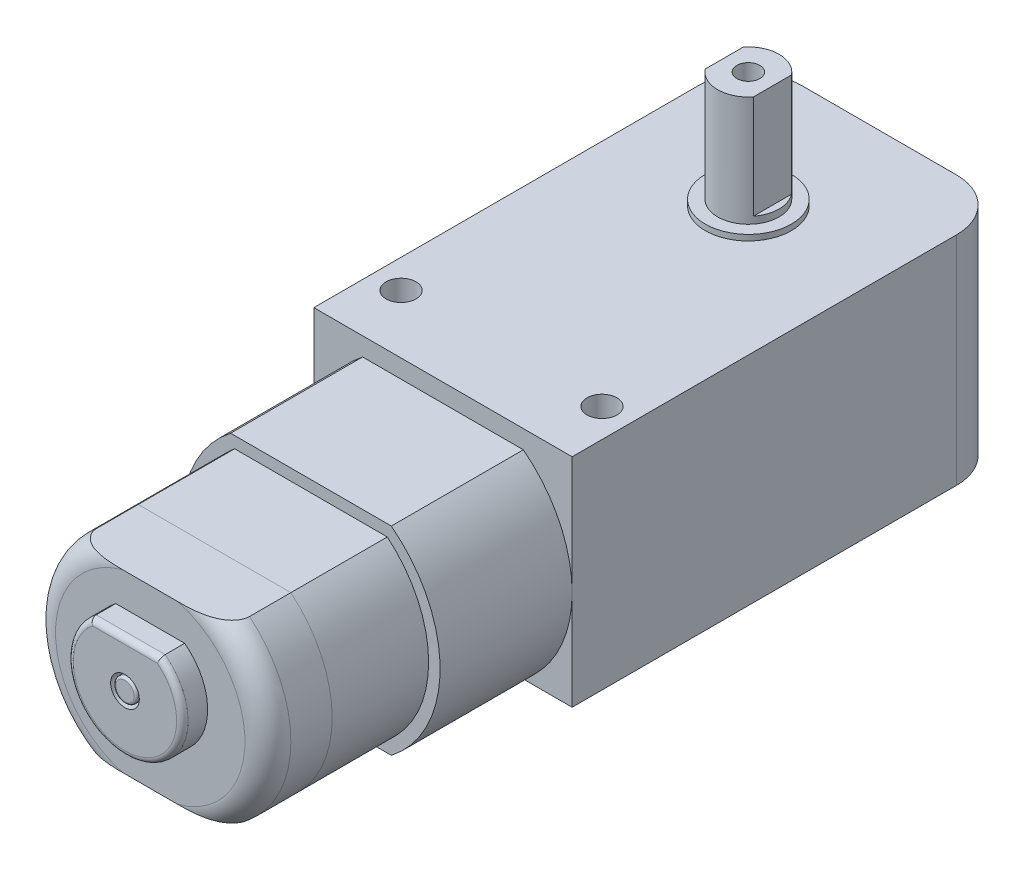
SolidWorks part; units mm, degrees
ref_plane "Front Plane" through (0, 0, 0) normal (0, 0, 1) x (1, 0, 0)
ref_plane "Top Plane" through (0, 0, 0) normal (0, 1, 0) x (1, 0, 0)
ref_plane "Right Plane" through (0, 0, 0) normal (1, 0, 0) x (0, 0, -1)
sketch "Sketch1" plane through (0, 0, 0) normal (0, 1, 0) x (1, 0, 0)
  line L1 (11.25, 19) -> (-11.25, 19)
  line L2 (11.25, 19) -> (11.25, -19)
  line L3 (11.25, -19) -> (-11.25, -19)
  line L4 (-11.25, 19) -> (-11.25, -19)
  line L5 (11.25, 19) -> (-11.25, -19) construction
  line L6 (11.25, -19) -> (-11.25, 19) construction
  point P0 (0, 0)
  dimension "D1" = 22.5
  dimension "D2" = 38
extrude "Boss-Extrude1" add sketch "Sketch1" along normal mid plane 18.9
fillet "Fillet1" radius 4.5 2 edges at (-11.25, 0, -19) (11.25, 0, -19)
sketch "Sketch2" plane through (0, 0, 19) normal (0, 0, 1) x (1, 0, 0)
  line L0 (-11.25, -9.45) -> (11.25, -9.45) construction
  line L5 (7, -9.45) -> (-7, -9.45)
  line L7 (7, 7.85) -> (-7, 7.85)
  line L9 (7, -9.45) -> (-7, 7.85) construction
  line L10 (7, 7.85) -> (-7, -9.45) construction
  line L13 (-11.25, 9.45) -> (-11.25, -9.45) construction
  arc A0 (-7, 7.85) -> (-7, -9.45) centre (-0.3224, -0.8) ccw
  arc A1 (7, 7.85) -> (7, -9.45) centre (0.3224, -0.8) cw
  point P0 (0, -0.8)
  point P5 (0, 0)
  point P10 (0, 0)
  point P11 (0, 0)
  point P12 (0, -0.8)
  point P13 (0, 0)
  point P14 (0, 0)
  point P15 (0, 0)
  point P18 (-2.3599, -0.8)
  dimension "D3" = 10.9276
  dimension "D1" = 17.3
  dimension "D2" = 14
extrude "Boss-Extrude2" add sketch "Sketch2" along normal blind 11.5
sketch "Sketch3" plane through (0, 0, 30.5) normal (0, 0, 1) x (1, 0, 0)
  line L4 (-6.6497, -8.45) -> (6.6497, -8.45)
  line L5 (6.6497, 6.85) -> (-6.6497, 6.85)
  line L6 (-6.6497, -8.45) -> (6.6497, -8.45)
  line L7 (6.6497, 6.85) -> (-6.6497, 6.85)
  arc A4 (-6.6497, 6.85) -> (-6.6497, -8.45) centre (-0.3224, -0.8) ccw
  arc A5 (6.6497, -8.45) -> (6.6497, 6.85) centre (0.3224, -0.8) ccw
  arc A6 (-6.6497, 6.85) -> (-6.6497, -8.45) centre (-0.3224, -0.8) ccw
  arc A7 (6.6497, -8.45) -> (6.6497, 6.85) centre (0.3224, -0.8) ccw
  dimension "D1" = 1
extrude "Cut-Extrude1" cut sketch "Sketch3" against normal up to surface (11.5 mm away) up to face at (0, 5.6646, 19)
sketch "Sketch4" plane through (0, 0, 0) normal (0, 1, 0) x (1, 0, 0)
  line L0 (6.75, 19) -> (-6.75, 19) construction
  line L1 (2.5, 19) -> (-2.5, 19)
  line L2 (2.5, 19) -> (2.5, 24)
  line L3 (2.5, 24) -> (-2.5, 24)
  line L4 (-2.5, 19) -> (-2.5, 24)
  line L5 (2.5, 19) -> (-2.5, 24) construction
  line L6 (2.5, 24) -> (-2.5, 19) construction
  circle A0 centre (0, 21.5) radius 1.25
  point P0 (0, 21.5)
  point P5 (-2.5, 19)
  dimension "D3" = 2.5
  dimension "D1" = 5
  dimension "D2" = 5
extrude "Boss-Extrude3" add sketch "Sketch4" along normal mid plane 2.5 contours L4 L1 L2 L3 A0
sketch "Sketch5" plane through (0, 9.45, 0) normal (0, 1, 0) x (1, 0, 0)
  line L0 (0, 24) -> (0, 0) construction
  line L1 (2.5, 24) -> (-2.5, 24) construction
  line L2 (6.75, 19) -> (-6.75, 19) construction
  circle A0 centre (0, 7.6) radius 3.75
  point P7 (0, 11.0568)
  dimension "D1" = 7.5
  dimension "D2" = 11.4
extrude "Boss-Extrude4" add sketch "Sketch5" along normal blind 0.5
sketch "Sketch6" plane through (0, 9.95, 0) normal (0, 1, 0) x (1, 0, 0)
  circle A0 centre (0, 7.6) radius 2.675
  dimension "D1" = 5.35
extrude "Boss-Extrude5" add sketch "Sketch6" along normal blind 9.6
sketch "Sketch7" plane through (0, 19.55, 0) normal (0, 1, 0) x (1, 0, 0)
  line L0 (-2.1, 9.257) -> (-2.1, 5.943)
  line L1 (2.1, 9.257) -> (2.1, 5.943)
  line L2 (-2.1, 7.6) -> (2.1, 7.6) construction
  circle A0 centre (0, 7.6) radius 2.675 construction
  circle A1 centre (0, 7.6) radius 2.675 construction
  arc A2 (2.1, 5.943) -> (2.1, 9.257) centre (0, 7.6) ccw
  circle A3 centre (0, 7.6) radius 2.675
  arc A4 (-2.1, 9.257) -> (-2.1, 5.943) centre (0, 7.6) ccw
  point P10 (0, 7.6)
  point P12 (0, 0)
  dimension "D2" = 4.2
  dimension "D1" = 0
extrude "Cut-Extrude4" cut sketch "Sketch7" against normal blind 9
sketch "Sketch8" plane through (0, 19.55, 0) normal (0, 1, 0) x (1, 0, 0)
  circle A0 centre (0, 7.6) radius 1
  dimension "D1" = 2
extrude "Cut-Extrude5" cut sketch "Sketch8" against normal up to surface (9 mm away) up to face at (-2.3875, 10.55, -7.6)
fillet "Fillet2" radius 0.5 2 edges at (2.5, 0, -24) (-2.5, 0, -24)
sketch "Sketch9" plane through (0, 0, 19) normal (0, 0, 1) x (1, 0, 0)
  line L2 (-6.6497, -8.45) -> (6.6497, -8.45)
  line L3 (6.6497, 6.85) -> (-6.6497, 6.85)
  line L4 (-6.6497, -8.45) -> (6.6497, -8.45)
  line L5 (6.6497, 6.85) -> (-6.6497, 6.85)
  arc A2 (-6.6497, 6.85) -> (-6.6497, -8.45) centre (-0.3224, -0.8) ccw
  arc A3 (6.6497, -8.45) -> (6.6497, 6.85) centre (0.3224, -0.8) ccw
  arc A4 (-6.6497, 6.85) -> (-6.6497, -8.45) centre (-0.3224, -0.8) ccw
  arc A5 (6.6497, -8.45) -> (6.6497, 6.85) centre (0.3224, -0.8) ccw
  dimension "D1" = 0
extrude "Boss-Extrude6" add sketch "Sketch9" along normal blind 27.7 separate body
sketch "Sketch10" plane through (0, 6.85, 0) normal (0, 1, 0) x (1, 0, 0)
  line L0 (-10.25, -38.9) -> (10.25, -38.9)
  line L1 (-10.25, -19) -> (-10.25, -46.7) construction
  line L2 (10.25, -46.7) -> (10.25, -19) construction
  line L3 (7, -30.5) -> (-7, -30.5) construction
  dimension "D1" = 8.4
split "Split1" trim tools "Sketch10" bodies to split 109 resulting bodies 110 111
sketch "Sketch11" plane through (0, 0, 46.7) normal (0, 0, 1) x (1, 0, 0)
  line L0 (-3, 4) -> (3, 4)
  line L3 (-6.6497, -8.45) -> (6.6497, -8.45)
  line L4 (6.6497, 6.85) -> (-6.6497, 6.85)
  line L5 (-6.6497, -8.45) -> (6.6497, -8.45)
  line L6 (6.6497, 6.85) -> (-6.6497, 6.85)
  arc A0 (-3, 4) -> (3, 4) centre (0, 0) ccw
  arc A3 (-6.6497, 6.85) -> (-6.6497, -8.45) centre (-0.3224, -0.8) ccw
  arc A7 (-6.6497, 6.85) -> (-6.6497, -8.45) centre (-0.3224, -0.8) ccw
  arc A9 (6.6497, -8.45) -> (6.6497, 6.85) centre (0.3224, -0.8) ccw
  arc A10 (6.6497, -8.45) -> (6.6497, 6.85) centre (0.3224, -0.8) ccw
  dimension "D1" = 10
  dimension "D2" = 9
  dimension "D3" = 0
extrude "Cut-Extrude6" cut sketch "Sketch11" against normal blind 2.2
fillet "Fillet4" radius 0.5 2 edges at (0, -5, 46.7) (0, 4, 46.7)
fillet "Fillet3" radius 2 2 edges at (-10.25, -0.8, 44.5) (10.25, -0.8, 44.5)
sketch "Sketch12" plane through (0, 0, 46.7) normal (0, 0, 1) x (1, 0, 0)
  circle A0 centre (0, 0) radius 1.25
  dimension "D1" = 2.5
extrude "Cut-Extrude7" cut sketch "Sketch12" against normal up to surface (2.2 mm away) up to face at (0, -0.5, 44.5)
sketch "Sketch13" plane through (0, 0, 44.5) normal (0, 0, 1) x (1, 0, 0)
  circle A0 centre (0, 0) radius 1
  dimension "D1" = 2
extrude "Boss-Extrude7" add sketch "Sketch13" along normal up to surface (2.2 mm away) up to face at (1.25, 0, 46.7)
fillet "Fillet5" radius 0.2 1 edges at (1, 0, 46.7)
sketch "Sketch14" plane through (0, 9.45, 0) normal (0, 1, 0) x (1, 0, 0)
  line L0 (-8.75, -13.9) -> (8.75, -13.9) construction
  line L1 (11.25, -19) -> (11.25, 14.5) construction
  line L4 (7, -19) -> (11.25, -19) construction
  circle A0 centre (-8.75, -13.9) radius 1.3
  circle A1 centre (8.75, -13.9) radius 1.3
  point P10 (0, 0)
  point P11 (0, -13.9)
  dimension "D1" = 2.6
  dimension "D2" = 2.5
  dimension "D3" = 5.1
extrude "Cut-Extrude8" cut sketch "Sketch14" against normal up to surface (18.9 mm away) up to face at (0, -9.45, 6.8136)
equation "\"D2@Sketch14\"= 1.2 + (\"D1@Sketch14\"/2)"
equation "\"D3@Sketch14\"=3.8 + (\"D1@Sketch14\"/2)"
